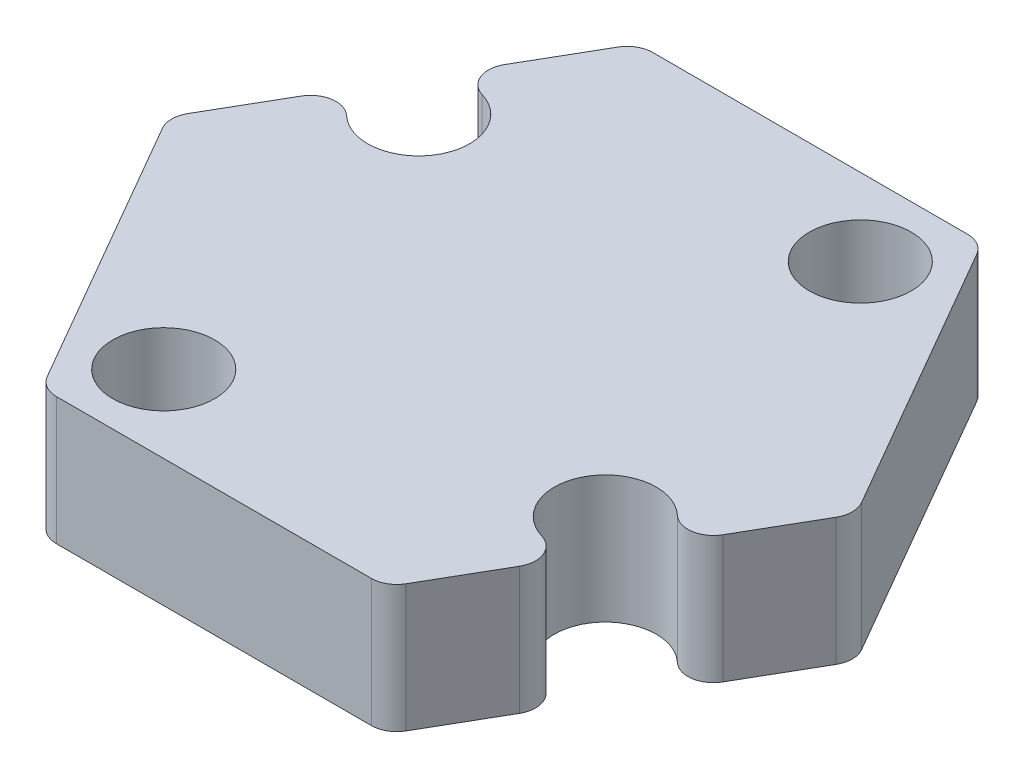
SolidWorks part; units mm, degrees
ref_plane "Спереди" through (0, 0, 0) normal (0, 0, 1) x (1, 0, 0)
ref_plane "Сверху" through (0, 0, 0) normal (0, 1, 0) x (1, 0, 0)
ref_plane "Справа" through (0, 0, 0) normal (1, 0, 0) x (0, 0, -1)
sketch "Эскиз1" plane through (0, 0, 0) normal (0, 1, 0) x (1, 0, 0)
  line L0 (0, 77.0654) -> (0, 0) construction
  line L1 (0, 0) -> (93.5211, 0) construction
  line L2 (0, 0) -> (6.75, 11.6913) construction
  line L3 (13.5, 0) -> (6.75, 11.6913)
  line L4 (6.75, 11.6913) -> (-6.75, 11.6913)
  line L5 (-6.75, 11.6913) -> (-13.5, 0)
  line L6 (-13.5, 0) -> (-6.75, -11.6913)
  line L7 (-6.75, -11.6913) -> (6.75, -11.6913)
  line L8 (6.75, -11.6913) -> (13.5, 0)
  circle A0 centre (0, 0) radius 13.5 construction
  point P21 (0, 0)
  dimension "D1" = 27
  dimension "D5" = 30
extrude "Бобышка-Вытянуть1" add sketch "Эскиз1" along normal blind 5
fillet "Скругление1" radius 1 6 edges at (-6.75, 2.5, -11.6913) (6.75, 2.5, -11.6913) (13.5, 2.5, 0) (6.75, 2.5, 11.6913) (-6.75, 2.5, 11.6913) (-13.5, 2.5, 0)
sketch "Эскиз2" plane through (0, 5, 0) normal (0, 1, 0) x (1, 0, 0)
  line L0 (0, 12.3571) -> (0, 0) construction
  line L1 (0, 0) -> (8.036, 13.9188) construction
  circle A0 centre (5, 8.6603) radius 2
  circle A1 centre (8.6603, -5) radius 2
  circle A2 centre (-5, -8.6603) radius 2
  circle A3 centre (-8.6603, 5) radius 2
  point P15 (0, 0)
  dimension "D2" = 10
  dimension "D1" = 30
  dimension "D3" = 4
extrude "Вырез-Вытянуть1" cut sketch "Эскиз2" against normal blind 10
fillet "Скругление2" radius 1 4 edges at (-10.6587, 2.5, -4.9213) (-9.5913, 2.5, -6.7701) (10.6587, 2.5, 4.9213) (9.5913, 2.5, 6.7701)
